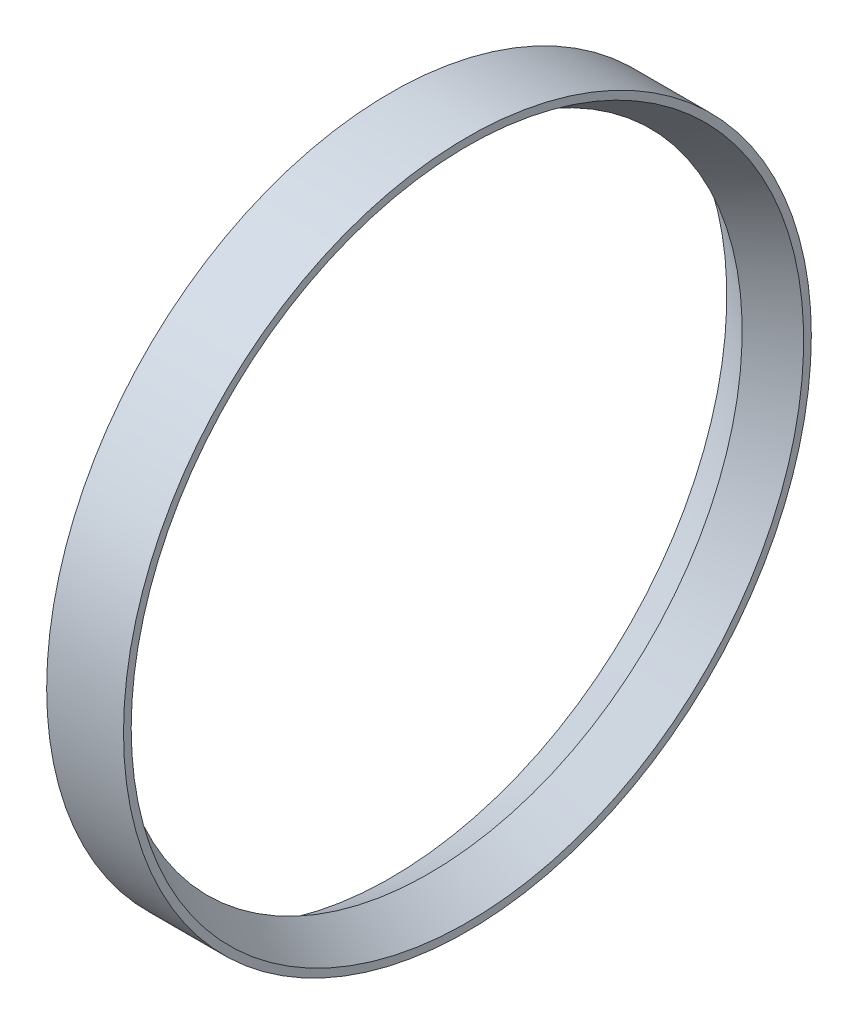
SolidWorks part; units mm, degrees
ref_plane "Front Plane" through (0, 0, 0) normal (0, 0, 1) x (1, 0, 0)
ref_plane "Top Plane" through (0, 0, 0) normal (0, 1, 0) x (1, 0, 0)
ref_plane "Right Plane" through (0, 0, 0) normal (1, 0, 0) x (0, 0, -1)
sketch "Sketch1" plane through (0, 0, 0) normal (1, 0, 0) x (0, 0, -1)
  line L0 (0, 0) -> (-35, 0) construction
  dimension "D1" = 35
sketch "Sketch2" plane through (0, 0, 0) normal (0, 1, 0) x (1, 0, 0)
  line L1 (0, 0) -> (0, -35) construction
  line L2 (4, -35) -> (0, -32.6)
  line L4 (-4, -35) -> (0, -32.6)
  line L5 (-4, -35) -> (-4, -35.8)
  line L6 (-4, -35.8) -> (4, -35.8)
  line L7 (4, -35.8) -> (4, -35)
  dimension "D1" = 0.8
sketch "Sketch3" plane through (0, 0, 0) normal (0, 1, 0) x (1, 0, 0)
  line L0 (0, 0) -> (14.0092, 0) construction
revolve "Revolve1" add sketch "Sketch2" angle 360 about L0
